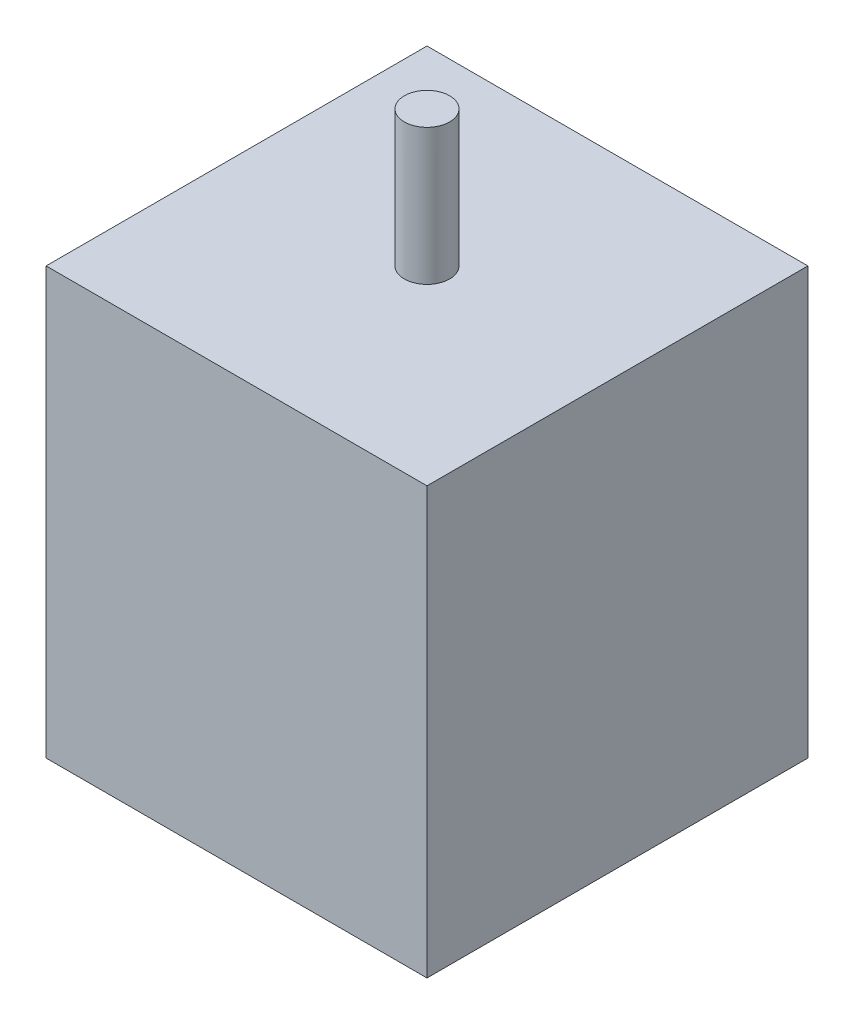
SolidWorks part; units mm, degrees
ref_plane "前视" through (0, 0, 0) normal (0, 0, 1) x (1, 0, 0)
ref_plane "上视" through (0, 0, 0) normal (0, 1, 0) x (1, 0, 0)
ref_plane "右视" through (0, 0, 0) normal (1, 0, 0) x (0, 0, -1)
sketch "Sketch1" plane through (0, 0, 0) normal (0, 1, 0) x (1, 0, 0)
  line L1 (0, 0) -> (42, 0)
  line L2 (0, 0) -> (0, 42)
  line L3 (0, 42) -> (42, 42)
  line L4 (42, 0) -> (42, 42)
  dimension "D1" = 42
  dimension "D2" = 42
extrude "Extrude1" add sketch "Sketch1" along normal blind 47
sketch "Sketch2" plane through (0, 47, 0) normal (0, 1, 0) x (1, 0, 0)
  circle A0 centre (21, 21) radius 2.5
extrude "Extrude2" add sketch "Sketch2" along normal blind 15
